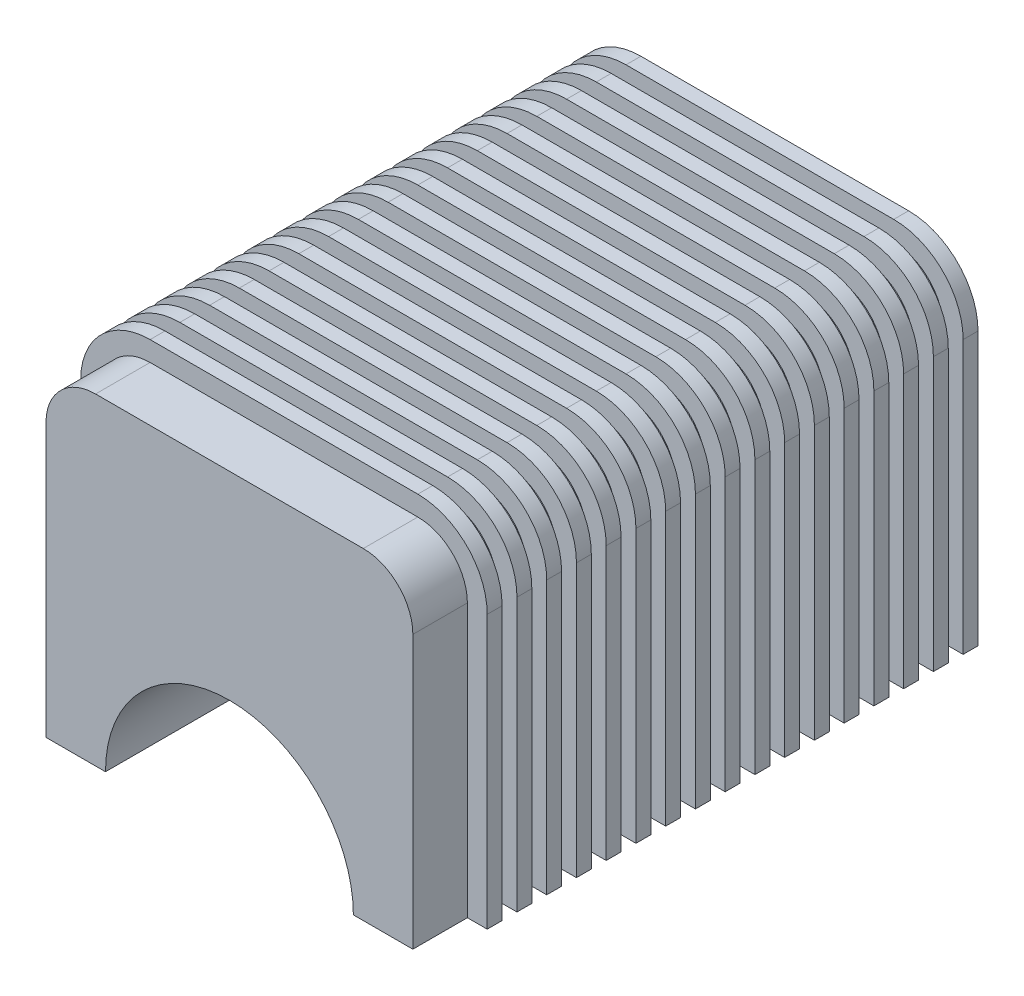
SolidWorks part; units mm, degrees
material "Malleable Cast Iron"
ref_plane "Front Plane" through (0, 0, 0) normal (0, 0, 1) x (1, 0, 0)
ref_plane "Top Plane" through (0, 0, 0) normal (0, 1, 0) x (1, 0, 0)
ref_plane "Right Plane" through (0, 0, 0) normal (1, 0, 0) x (0, 0, -1)
sketch "Sketch1" plane through (0, 0, 0) normal (0, 0, 1) x (1, 0, 0)
  line L0 (25, 0) -> (37, 0)
  line L1 (37, 0) -> (37, 55)
  line L2 (27, 65) -> (-27, 65)
  line L3 (-37, 55) -> (-37, 0)
  line L4 (-37, 0) -> (-25, 0)
  arc A0 (-25, 0) -> (25, 0) centre (0, 0) cw
  arc A1 (37, 55) -> (27, 65) centre (27, 55) ccw
  arc A2 (-27, 65) -> (-37, 55) centre (-27, 55) ccw
  point P4 (-17.7419, 0)
  point P11 (37, 65)
  dimension "D3" = 25
  dimension "D4" = 10
  dimension "D1" = 12
  dimension "D2" = 65
extrude "Boss-Extrude1" add sketch "Sketch1" along normal blind 110
sketch "Sketch2" plane through (0, 0, 0) normal (0, 0, -1) x (-1, 0, 0)
  line L9 (37, 0) -> (25, 0) construction
  line L10 (-25, 0) -> (-37, 0) construction
  line L12 (20.6155, -4) -> (41, -4)
  line L13 (41, -4) -> (41, 55)
  line L14 (27, 69) -> (-27, 69)
  line L15 (-41, 55) -> (-41, -4)
  line L16 (-41, -4) -> (-20.6155, -4)
  line L18 (41, 0) -> (41, 55)
  line L19 (27, 69) -> (-27, 69)
  line L20 (-41, 55) -> (-41, 0)
  line L24 (37, 0) -> (25, 0)
  line L25 (-25, 0) -> (-37, 0)
  line L27 (-37, 0) -> (-41, 0)
  line L28 (37, 0) -> (41, 0)
  arc A6 (25, 0) -> (-25, 0) centre (0, 0) ccw construction
  arc A7 (20.6155, -4) -> (-20.6155, -4) centre (0, 0) ccw
  arc A8 (41, 55) -> (27, 69) centre (27, 55) ccw
  arc A9 (-27, 69) -> (-41, 55) centre (-27, 55) ccw
  arc A11 (41, 55) -> (27, 69) centre (27, 55) ccw
  arc A12 (-27, 69) -> (-41, 55) centre (-27, 55) ccw
  arc A15 (25, 0) -> (-25, 0) centre (0, 0) ccw
  dimension "D1" = 4
extrude "Boss-Extrude2" add sketch "Sketch2" against normal blind 3
pattern_linear "LPattern1" count 17 spacing 6 along (0, 0, 1) of "Boss-Extrude2"
